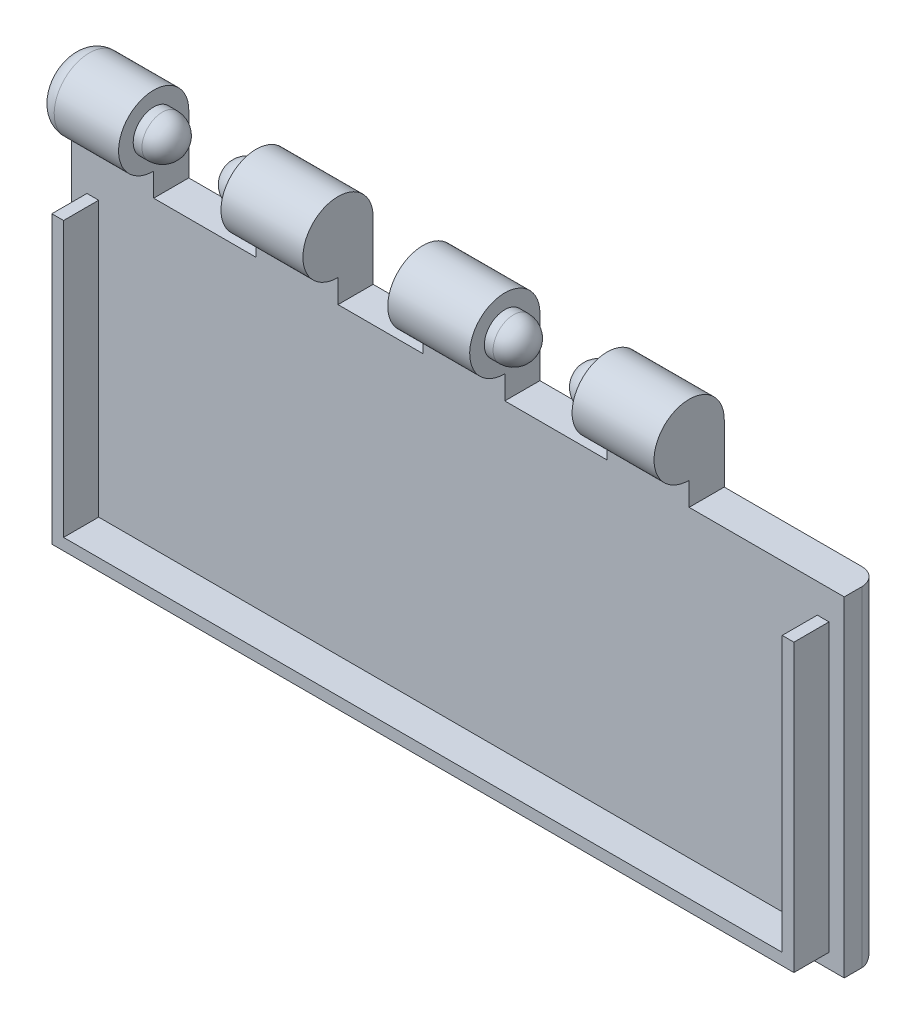
SolidWorks part; units mm, degrees
ref_plane "Front Plane" through (0, 0, 0) normal (0, 0, 1) x (1, 0, 0)
ref_plane "Top Plane" through (0, 0, 0) normal (0, 1, 0) x (1, 0, 0)
ref_plane "Right Plane" through (0, 0, 0) normal (1, 0, 0) x (0, 0, -1)
sketch "Sketch1" plane through (0, 0, 0) normal (0, 0, 1) x (1, 0, 0)
  line L1 (-33, -14.1) -> (33, -14.1)
  line L2 (-33, -14.1) -> (-33, 14.1)
  line L3 (-33, 14.1) -> (33, 14.1)
  line L4 (33, -14.1) -> (33, 14.1)
  line L5 (-33, -14.1) -> (33, 14.1) construction
  line L6 (-33, 14.1) -> (33, -14.1) construction
  point P0 (0, 0)
  dimension "D1" = 66
  dimension "D2" = 28.2
extrude "Boss-Extrude1" add sketch "Sketch1" along normal blind 3
sketch "Sketch10" plane through (-33, 0, 0) normal (-1, 0, 0) x (0, 0, 1)
  line L0 (3, 14.1) -> (3, 19.1) construction
  line L3 (0, 19.1) -> (0, 14.1)
  line L4 (0, 14.1) -> (3, 14.1)
  line L5 (3, 14.1) -> (3, 16.1)
  arc A1 (3, 16.1) -> (0, 19.1) centre (3, 19.1) ccw
  dimension "D1" = 5
  dimension "D2" = 6
extrude "Boss-Extrude4" add sketch "Sketch10" against normal blind 7
sketch "Sketch17" plane through (-26, 0, 0) normal (1, 0, 0) x (0, 0, -1)
  circle A0 centre (-3, 19.1) radius 1.75
  dimension "D1" = 3.5
extrude "Boss-Extrude7" add sketch "Sketch17" along normal blind 0.75
sketch "Sketch18" plane through (-25.25, 0, 0) normal (1, 0, 0) x (0, 0, -1)
  line L0 (-3, 20.85) -> (-3, 17.35)
  arc A0 (-3, 17.35) -> (-3, 20.85) centre (-3, 19.1) ccw
  dimension "D1" = 3.5
revolve "Revolve4" add sketch "Sketch18" angle 180 about L0
sketch "Sketch19" plane through (0, 14.1, 0) normal (0, 1, 0) x (1, 0, 0)
  line L0 (-23.5, -3) -> (-21.625, -3) construction
  line L1 (33, -3) -> (-26, -3) construction
  line L2 (-21.625, -3) -> (-21.625, 0) construction
  line L3 (33, 0) -> (-26, 0) construction
  arc A0 (-25.25, -4.75) -> (-25.25, -1.25) centre (-25.25, -3) ccw construction
  dimension "D1" = 1.875
ref_plane "Plane1" through (-21.625, 0, 0) normal (1, 0, 0) x (0, 0, -1)
mirror "Mirror1" about plane through (-21.625, 0, 0) normal (1, 0, 0) of "Boss-Extrude4", "Boss-Extrude7", "Revolve4"
pattern_linear "LPattern2" count 2 spacing 30 along (1, 0, 0) of "Boss-Extrude4", "Boss-Extrude7", "Revolve4", "Mirror1"
fillet "Fillet5" radius 1.5 4 edges at (-33, 2.5, 0) (0, -14.1, 0) (33, 0, 0) (-33, 21.2213, 5.1213)
sketch "Sketch9" plane through (0, 0, 3) normal (0, 0, 1) x (1, 0, 0)
  line L0 (-33, 11.6) -> (-31.7, 11.6) construction
  line L1 (-33, 17.6) -> (-33, -14.1) construction
  line L2 (-31.7, -14.1) -> (-31.7, 11.6) construction
  line L3 (-33, -14.1) -> (33, -14.1) construction
  line L4 (33, 11.6) -> (31.7, 11.6) construction
  line L5 (33, -14.1) -> (33, 14.1) construction
  line L6 (31.7, -14.1) -> (31.7, -12.85) construction
  line L7 (31.7, 11.6) -> (31.7, -12.85) construction
  line L8 (31.7, -12.85) -> (-31.7, -12.85) construction
  line L9 (33, 14.1) -> (19.75, 14.1) construction
  line L11 (-31.7, 11.6) -> (-30.7, 11.6)
  line L12 (-31.7, 11.6) -> (-31.7, -12.85)
  line L13 (-31.7, -12.85) -> (-30.7, -12.85)
  line L14 (-30.7, 11.6) -> (-30.7, -11.85)
  line L15 (-30.7, -11.85) -> (30.7, -11.85)
  line L17 (-30.7, -12.85) -> (31.7, -12.85)
  line L18 (31.7, -11.85) -> (31.7, -12.85)
  line L19 (31.7, 11.6) -> (30.7, 11.6)
  line L20 (31.7, 11.6) -> (31.7, -11.85)
  line L22 (30.7, 11.6) -> (30.7, -11.85)
  dimension "D1" = 1.3
  dimension "D2" = 1.3
  dimension "D3" = 1.25
  dimension "D4" = 2.5
  dimension "D5" = 2.5
  dimension "D6" = 1
  dimension "D7" = 1
  dimension "D8" = 1
  dimension "D9" = 1
extrude "Boss-Extrude3" add sketch "Sketch9" along normal blind 3
